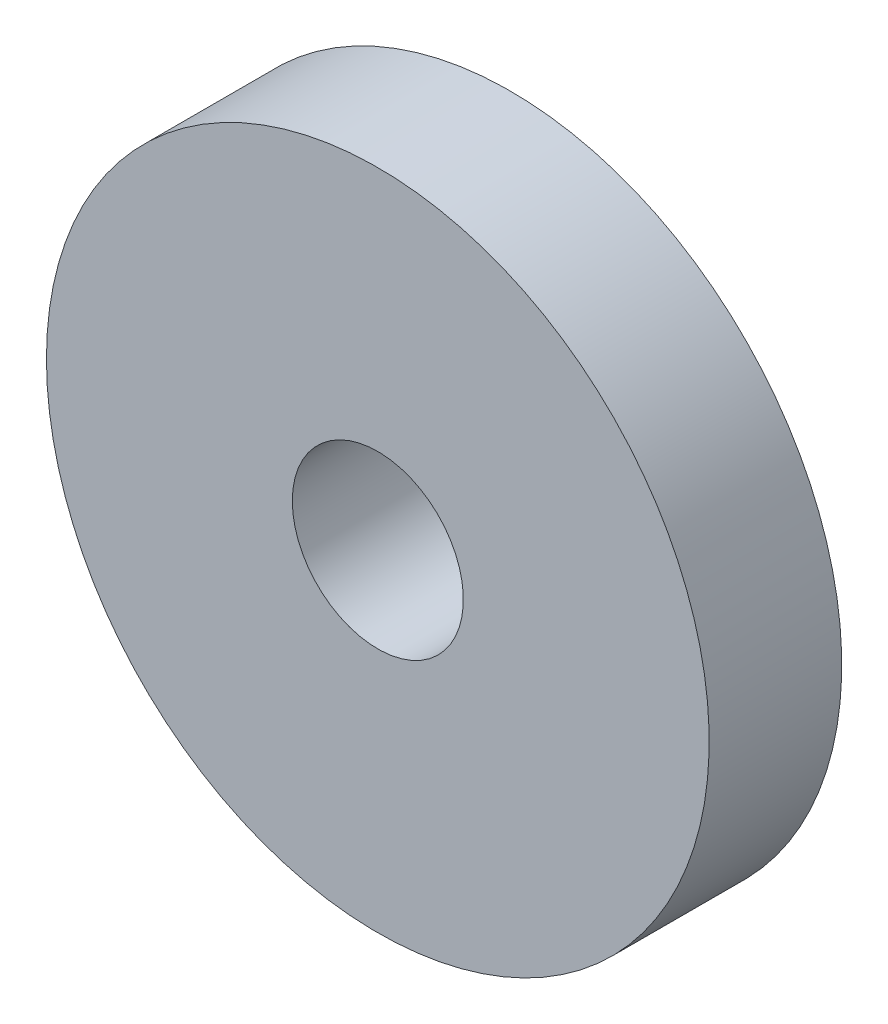
SolidWorks part; units mm, degrees
ref_plane "Front Plane" through (0, 0, 0) normal (0, 0, 1) x (1, 0, 0)
ref_plane "Top Plane" through (0, 0, 0) normal (0, 1, 0) x (1, 0, 0)
ref_plane "Right Plane" through (0, 0, 0) normal (1, 0, 0) x (0, 0, -1)
sketch "Sketch1" plane through (0, 0, 0) normal (0, 0, 1) x (1, 0, 0)
  circle A0 centre (0, 0) radius 15.5
  circle A1 centre (0, 0) radius 4
  dimension "D1" = 8
  dimension "D2" = 31
extrude "Boss-Extrude1" add sketch "Sketch1" along normal blind 6.2
